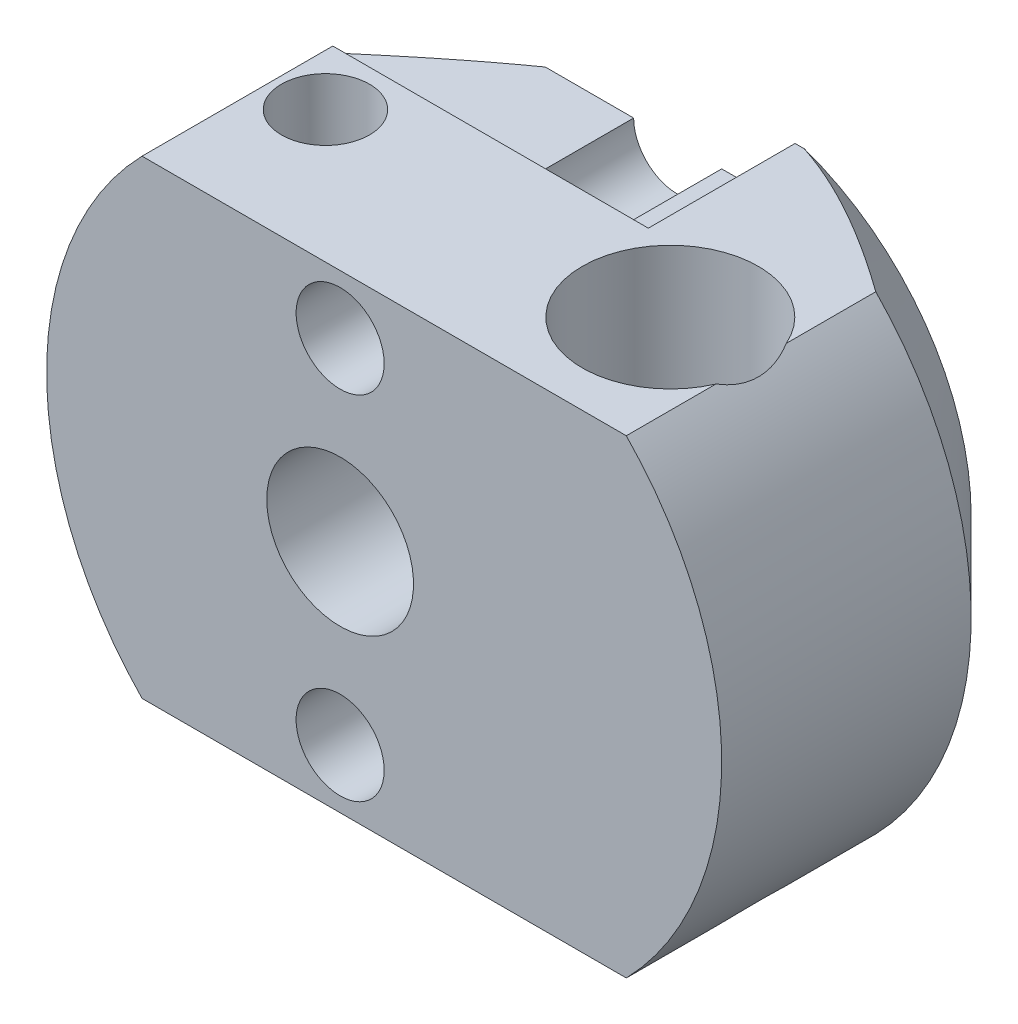
SolidWorks part; units mm, degrees
ref_plane "Спереди" through (0, 0, 0) normal (0, 0, 1) x (1, 0, 0)
ref_plane "Сверху" through (0, 0, 0) normal (0, 1, 0) x (1, 0, 0)
ref_plane "Справа" through (0, 0, 0) normal (1, 0, 0) x (0, 0, -1)
ref_plane "Плоскость1" through (0, 0, 0) normal (0, 0, -1) x (-1, 0, 0)
sketch "Эскиз1" plane through (0, 0, 0) normal (0, 0, -1) x (-1, 0, 0)
  line L0 (6.75, 8) -> (-9.75, 8)
  line L1 (-9.75, -8) -> (6.75, -8)
  arc A0 (6.75, -8) -> (6.75, 8) centre (-1.4712, 0) ccw
  arc A1 (-9.75, 8) -> (-9.75, -8) centre (-1.5288, 0) ccw
extrude "Бобышка-Вытянуть1" add sketch "Эскиз1" against normal blind 11.5
sketch "Эскиз2" plane through (0, 0, 0) normal (0, 0, -1) x (-1, 0, 0)
  line L0 (-4, 6) -> (8.3057, 6)
  line L1 (6.75, 8) -> (-4, 8)
  line L2 (-4, 8) -> (-4, 6)
  arc A0 (8.3057, 6) -> (6.75, 8) centre (-1.4712, 0) ccw
extrude "Вырез-Вытянуть1" cut sketch "Эскиз2" against normal blind 5
sketch "Эскиз3" plane through (0, 0, 0) normal (0, 0, -1) x (-1, 0, 0)
  line L0 (8.3057, -6) -> (-4, -6)
  line L1 (-4, -6) -> (-4, -8)
  line L2 (-4, -8) -> (6.75, -8)
  arc A0 (6.75, -8) -> (8.3057, -6) centre (-1.4712, 0) ccw
extrude "Вырез-Вытянуть2" cut sketch "Эскиз3" against normal blind 5
hole_wizard "Диаметр отверстия Ø3.0 (3)1" positions "Эскиз5" profile "Эскиз4" hole size "Ø3.0" standard "Ansi Metric"
sketch "Эскиз5" plane through (0, 0, 11.5) normal (0, 0, 1) x (1, 0, 0)
  point P0 (0, -6)
  point P1 (0, 6)
sketch "Эскиз4" plane through (0, -6, 11.5) normal (1, 0, 0) x (0, -1, 0)
  line L0 (0, 0) -> (0, 11.5)
  line L1 (0, 11.5) -> (1.5, 11.5)
  line L2 (1.5, 11.5) -> (1.5, 0)
  line L5 (1.5, 0) -> (0, 0)
  line L11 (0, -6.35) -> (0, 107.95) construction
  dimension "Диаметр сквозного отверстия" = 3
  dimension "Глубина сквозного отверстия" = 11.5
hole_wizard "Диаметр отверстия Ø3.0 (3)2" positions "Эскиз7" profile "Эскиз6" hole size "Ø3.0" standard "Ansi Metric"
sketch "Эскиз7" plane through (0, 8, 0) normal (0, 1, 0) x (1, 0, 0)
  point P0 (-5, -7)
sketch "Эскиз6" plane through (-5, 8, 7) normal (1, 0, 0) x (0, 0, 1)
  line L0 (0, 0) -> (0, 16)
  line L1 (0, 16) -> (1.5, 16)
  line L2 (1.5, 16) -> (1.5, 0)
  line L5 (1.5, 0) -> (0, 0)
  line L11 (0, -6.35) -> (0, 107.95) construction
  dimension "Диаметр сквозного отверстия" = 3
  dimension "Глубина сквозного отверстия" = 16
hole_wizard "Диаметр отверстия Ø2.5 (2.5)1" positions "Эскиз9" profile "Эскиз8" hole size "Ø2.5" standard "Ansi Metric"
sketch "Эскиз9" plane through (0, 0, 0) normal (0, 0, -1) x (-1, 0, 0)
  point P0 (5, 0)
sketch "Эскиз8" plane through (-5, 0, 0) normal (1, 0, 0) x (0, 1, 0)
  line L0 (0, 0) -> (0, 5.5)
  line L1 (0, 5.5) -> (1.25, 5.5)
  line L2 (1.25, 5.5) -> (1.25, 0)
  line L5 (1.25, 0) -> (0, 0)
  line L11 (0, -6.35) -> (0, 107.95) construction
  dimension "Диаметр сквозного отверстия" = 2.5
  dimension "Глубина сквозного отверстия" = 5.5
hole_wizard "Диаметр отверстия Ø5.0 (5)1" positions "Эскиз11" profile "Эскиз10" hole size "Ø5.0" standard "Ansi Metric"
sketch "Эскиз11" plane through (0, 0, 0) normal (0, 0, -1) x (-1, 0, 0)
  point P0 (0, 0)
sketch "Эскиз10" plane through (0, 0, 0) normal (1, 0, 0) x (0, 1, 0)
  line L0 (0, 0) -> (0, 11.5)
  line L1 (0, 11.5) -> (2.5, 11.5)
  line L2 (2.5, 11.5) -> (2.5, 0)
  line L5 (2.5, 0) -> (0, 0)
  line L11 (0, -6.35) -> (0, 107.95) construction
  dimension "Диаметр сквозного отверстия" = 5
  dimension "Глубина сквозного отверстия" = 11.5
hole_wizard "Диаметр отверстия Ø6.0 (6)1" positions "Эскиз13" profile "Эскиз12" hole size "Ø6.0" standard "Ansi Metric"
sketch "Эскиз13" plane through (0, -8, 0) normal (0, -1, 0) x (-1, 0, 0)
  point P0 (-7, -7.25)
sketch "Эскиз12" plane through (7, -8, 7.25) normal (1, 0, 0) x (0, 0, -1)
  line L0 (0, 0) -> (0, 16)
  line L1 (0, 16) -> (3, 16)
  line L2 (3, 16) -> (3, 0)
  line L5 (3, 0) -> (0, 0)
  line L11 (0, -6.35) -> (0, 107.95) construction
  dimension "Диаметр сквозного отверстия" = 6
  dimension "Глубина сквозного отверстия" = 16
hole_wizard "Диаметр отверстия Ø2.5 (2.5)2" positions "Эскиз15" profile "Эскиз14" hole size "Ø2.5" standard "Ansi Metric"
sketch "Эскиз15" plane through (0, 0, 0) normal (0, 0, -1) x (-1, 0, 0)
  point P0 (-7, 0)
sketch "Эскиз14" plane through (7, 0, 0) normal (1, 0, 0) x (0, 1, 0)
  line L0 (0, 0) -> (0, 4.25)
  line L1 (0, 4.25) -> (1.25, 4.25)
  line L2 (1.25, 4.25) -> (1.25, 0)
  line L5 (1.25, 0) -> (0, 0)
  line L11 (0, -6.35) -> (0, 107.95) construction
  dimension "Диаметр сквозного отверстия" = 2.5
  dimension "Глубина сквозного отверстия" = 4.25
chamfer "Фаска1" distance 3 angle 45 2 edges at (13, 0, 0) (-10, 0, 0)
